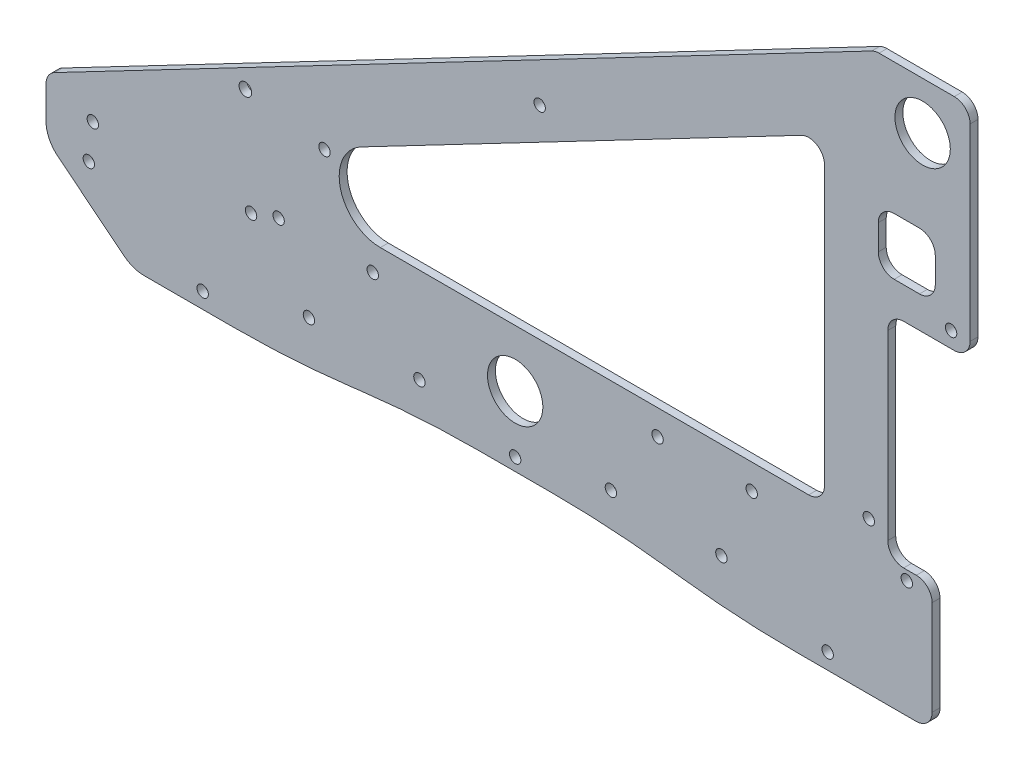
SolidWorks part; units mm, degrees
ref_plane "Front Plane" through (0, 0, 0) normal (0, 0, 1) x (1, 0, 0)
ref_plane "Top Plane" through (0, 0, 0) normal (0, 1, 0) x (1, 0, 0)
ref_plane "Right Plane" through (0, 0, 0) normal (1, 0, 0) x (0, 0, -1)
sketch "Sketch1" plane through (0, 0, 0) normal (0, 0, 1) x (1, 0, 0)
  line L1 (0, 0) -> (-355.6, 0)
  line L2 (0, 0) -> (0, 50.8)
  line L3 (0, 50.8) -> (-355.6, 50.8)
  line L4 (-355.6, 0) -> (-355.6, 50.8)
  line L5 (-167.3225, 6.35) -> (-167.3225, 34.29) construction
  line L6 (-292.735, 6.35) -> (-41.91, 6.35) construction
  circle A0 centre (-41.91, 6.35) radius 2.286
  circle A2 centre (-292.735, 6.35) radius 2.286
  circle A5 centre (-205.74, 19.05) radius 2.286
  circle A6 centre (-167.3225, 34.29) radius 11.1125
  circle A7 centre (-250.0852, 18.5066) radius 2.286
  circle A8 centre (-84.5598, 18.5066) radius 2.286
  circle A10 centre (-128.905, 19.05) radius 2.286
  circle A11 centre (-338.4153, 28.575) radius 2.286
  dimension "D3" = 125.4125
  dimension "D5" = 4.572
  dimension "D6" = 38.4175
  dimension "D9" = 15.7834
  dimension "D10" = 22.225
  dimension "D11" = 4.572
  dimension "D14" = 28.575
  dimension "D1" = 50.8
  dimension "D2" = 355.6
  dimension "D4" = 27.94
  dimension "D7" = 15.24
  dimension "D8" = 82.7627
  dimension "D12" = 167.3225
  dimension "D13" = 34.29
  dimension "D15" = 50.8
extrude "Bottom 2\"" add sketch "Sketch1" along normal blind 3.175
sketch "Sketch2" plane through (0, 0, 3.175) normal (0, 0, 1) x (1, 0, 0)
  line L0 (-384.175, 50.8) -> (-320.675, 0)
  line L1 (0, 50.8) -> (-355.6, 50.8) construction
  line L3 (-384.175, 50.8) -> (-384.175, 0)
  line L4 (-384.175, 0) -> (-320.675, 0)
  line L8 (0, 0) -> (-355.6, 0) construction
  dimension "D1" = 63.5
  dimension "D2" = 320.675
extrude "Cut-Extrude1" cut sketch "Sketch2" against normal through all
fillet "Fillet1" radius 12.7 2 edges at (-320.675, 0, 1.5875) (-355.6, 27.94, 1.5875)
sketch "Sketch3" plane through (0, 0, 3.175) normal (0, 0, 1) x (1, 0, 0)
  line L0 (-256.54, 0) -> (-205.74, 6.35)
  line L2 (-205.74, 6.35) -> (-128.905, 6.35)
  line L3 (-128.905, 6.35) -> (-78.105, 0)
  line L4 (-78.105, 0) -> (-256.54, 0)
  line L5 (0, 0) -> (-316.2201, 0) construction
  point P4 (-128.905, 19.05)
  point P7 (-205.74, 19.05)
  dimension "D1" = 50.8
  dimension "D2" = 50.8
  dimension "D3" = 12.7
extrude "Bottom Cutout" cut sketch "Sketch3" against normal through all
sketch "Sketch5" plane through (0, 0, 3.175) normal (0, 0, 1) x (1, 0, 0)
  line L0 (15.24, 50.8) -> (15.24, 224.79)
  line L1 (15.24, 224.79) -> (-22.86, 224.79)
  line L2 (-355.6, 50.8) -> (-22.86, 224.79)
  line L4 (0, 50.8) -> (-355.6, 50.8) construction
  line L5 (-355.6, 50.8) -> (15.24, 50.8)
  line L8 (0, 0) -> (-78.105, 0) construction
  line L9 (0, 0) -> (0, 50.8) construction
  circle A0 centre (-3.81, 205.74) radius 11.1125
  dimension "D3" = 22.225
  dimension "D1" = 38.1
  dimension "D2" = 19.05
  dimension "D4" = 205.74
  dimension "D5" = 3.81
  dimension "D6" = 19.05
extrude "Upper Triangle" add sketch "Sketch5" against normal up to surface (3.175 mm away) up to face at (-336.1293, 28.575, 0)
sketch "Sketch6" plane through (0, 0, 3.175) normal (0, 0, 1) x (1, 0, 0)
  circle A0 centre (-110.1725, 46.99) radius 2.286
  circle A1 centre (-167.3225, 11.43) radius 2.286
  circle A2 centre (-224.4725, 46.99) radius 2.286
  dimension "D1" = 4.572
  dimension "D2" = 114.3
  dimension "D3" = 46.99
  dimension "D4" = 110.1725
  dimension "D5" = 57.15
  dimension "D6" = 35.56
extrude "Gearbox Holes" cut sketch "Sketch6" against normal through all
sketch "Sketch7" plane through (0, 0, 3.175) normal (0, 0, 1) x (1, 0, 0)
  line L0 (0, 0) -> (0, 50.8) construction
  line L1 (0, 0) -> (-78.105, 0) construction
  circle A0 centre (-25.4, 60.96) radius 2.286
  dimension "D3" = 4.572
  dimension "D1" = 25.4
  dimension "D2" = 60.96
extrude "Cut-Extrude4" cut sketch "Sketch7" against normal through all
sketch "Sketch8" plane through (0, 0, 3.175) normal (0, 0, 1) x (1, 0, 0)
  line L0 (1.27, 172.085) -> (-21.59, 172.085)
  line L1 (15.24, 50.8) -> (-17.78, 50.8)
  line L2 (15.24, 50.8) -> (15.24, 136.525)
  line L4 (-17.78, 50.8) -> (-17.78, 136.525)
  line L5 (-17.78, 136.525) -> (15.24, 136.525)
  line L6 (-22.86, 224.79) -> (-355.6, 50.8) construction
  line L7 (0, 0) -> (-78.105, 0) construction
  line L8 (15.24, 224.79) -> (-22.86, 224.79) construction
  line L9 (-43.18, 185.5017) -> (-43.18, 57.15)
  line L10 (-43.18, 57.15) -> (-288.641, 57.15)
  line L11 (-288.641, 57.15) -> (-43.18, 185.5017)
  line L12 (-256.54, 0) -> (-316.2201, 0) construction
  line L13 (15.24, 50.8) -> (15.24, 224.79) construction
  line L14 (15.24, 50.8) -> (15.24, 224.79) construction
  line L15 (1.27, 172.085) -> (1.27, 149.225)
  line L16 (-21.59, 172.085) -> (-21.59, 149.225)
  line L17 (1.27, 149.225) -> (-21.59, 149.225)
  circle A1 centre (7.62, 142.875) radius 2.286
  circle A2 centre (-157.48, 138.6325) radius 2.286
  point P19 (-25.4, 60.96)
  dimension "D14" = 22.86
  dimension "D16" = 4.572
  dimension "D1" = 7.62
  dimension "D2" = 50.8
  dimension "D3" = 88.265
  dimension "D4" = 57.15
  dimension "D5" = 25.4
  dimension "D6" = 25.4
  dimension "D7" = 22.86
  dimension "D9" = 12.7
  dimension "D10" = 13.97
  dimension "D12" = 6.35
  dimension "D13" = 7.62
  dimension "D15" = 11.43
  dimension "D17" = 114.3
extrude "Cut-Extrude5" cut sketch "Sketch8" against normal through all
sketch "Sketch9" plane through (0, 0, 0) normal (0, 0, -1) x (-1, 0, 0)
  circle A0 centre (10.16, 46.99) radius 2.286
  circle A1 centre (72.39, 46.99) radius 2.286
  dimension "D1" = 4.572
extrude "Cut-Extrude6" cut sketch "Sketch9" against normal through all
fillet "Fillet2" radius 6.35 7 edges at (-355.6, 50.8, 1.5875) (-43.18, 185.5017, 1.5875) (-43.18, 57.15, 1.5875) (-17.78, 136.525, 1.5875) (-22.86, 224.79, 1.5875) (15.24, 224.79, 1.5875) (15.24, 136.525, 1.5875)
fillet "Fillet3" radius 6.35 4 edges at (1.27, 149.225, 1.5875) (1.27, 172.085, 1.5875) (-21.59, 172.085, 1.5875) (-21.59, 149.225, 1.5875)
sketch "Sketch10" [suppressed] plane through (0, 0, 3.175) normal (0, 0, 1) x (1, 0, 0)
  line L0 (-355.6, 50.8) -> (-43.18, 50.8)
  line L1 (-43.18, 50.8) -> (-43.18, 149.225)
  line L3 (-43.18, 149.225) -> (15.24, 149.225)
  line L4 (15.24, 136.525) -> (15.24, 224.79) construction
  line L6 (15.24, 149.225) -> (15.24, 224.79)
  line L7 (15.24, 224.79) -> (-22.86, 224.79)
  line L8 (-22.86, 224.79) -> (-355.6, 50.8)
  line L9 (-43.18, 57.15) -> (-43.18, 185.5017) construction
  line L10 (-21.59, 149.225) -> (1.27, 149.225) construction
extrude "Cut-Extrude7" [suppressed] cut sketch "Sketch10" against normal blind 5.08
sketch "Sketch11" plane through (0, 0, -43.815) normal (0, 0, -1) x (-1, 0, 0)
  line L0 (43.18, 63.5) -> (43.18, 175.0156) construction
  line L2 (96.52, 50.8) -> (96.52, 86.995)
  line L3 (96.52, 86.995) -> (157.1625, 86.995)
  line L4 (157.1625, 50.8) -> (157.1625, 86.995)
  line L5 (167.3225, 111.252) -> (167.3225, 34.29) construction
  line L6 (177.4825, 50.8) -> (177.4825, 86.995)
  line L7 (238.125, 86.995) -> (177.4825, 86.995)
  line L8 (238.125, 50.8) -> (238.125, 86.995)
  line L10 (15.24, 149.225) -> (5.08, 149.225) construction
  line L11 (43.18, 149.225) -> (167.3712, 149.225)
  line L12 (167.3712, 149.225) -> (282.575, 88.9848)
  line L13 (282.575, 88.9848) -> (282.575, 50.8)
  line L14 (282.575, 50.8) -> (238.125, 50.8)
  line L15 (157.1625, 50.8) -> (177.4825, 50.8)
  line L16 (43.18, 149.225) -> (43.18, 50.8)
  line L17 (43.18, 50.8) -> (96.52, 50.8)
  line L18 (157.1625, 50.8) -> (177.4825, 50.8)
  line L19 (0, 0) -> (78.105, 0) construction
  line L20 (43.18, 63.5) -> (43.18, 175.0156) construction
  line L21 (352.1924, 52.5818) -> (24.2424, 224.0671) construction
  line L22 (52.4724, 180.6427) -> (288.641, 57.15) construction
  line L23 (43.18, 136.525) -> (136.8435, 136.525)
  line L24 (43.18, 136.525) -> (43.18, 63.5)
  line L25 (83.82, 94.615) -> (101.2835, 94.615)
  line L26 (136.8435, 136.525) -> (101.2835, 94.615)
  line L29 (43.18, 63.5) -> (83.82, 63.5)
  line L30 (83.82, 94.615) -> (83.82, 63.5)
  circle A0 centre (167.3225, 111.252) radius 10.16
  circle A1 centre (157.48, 138.6325) radius 2.286
  circle A2 centre (90.17, 88.265) radius 2.286
  dimension "D4" = 4.572
  dimension "D5" = 20.32
  dimension "D16" = 4.572
  dimension "D1" = 10.16
  dimension "D2" = 96.52
  dimension "D3" = 36.195
  dimension "D6" = 44.45
  dimension "D8" = 50.8
  dimension "D9" = 12.7
  dimension "D10" = 7.62
  dimension "D11" = 12.7
  dimension "D12" = 12.7
  dimension "D13" = 35.56
  dimension "D14" = 6.35
  dimension "D15" = 6.35
extrude "Boss-Extrude3" [suppressed] add sketch "Sketch11" against normal blind 3.175
sketch "Sketch16" plane through (0, 0, 3.175) normal (0, 0, 1) x (1, 0, 0)
  line L0 (-224.4725, 46.99) -> (-262.255, 46.99) construction
  line L1 (-110.1725, 46.99) -> (-72.39, 46.99) construction
  circle A0 centre (-262.255, 46.99) radius 2.286
  dimension "D1" = 4.572
extrude "Cut-Extrude12" cut sketch "Sketch16" against normal through all
fillet "Fillet11" radius 16.51 1 edges at (-288.641, 57.15, 1.5875)
sketch "Sketch19" plane through (0, 0, 3.175) normal (0, 0, 1) x (1, 0, 0)
  line L2 (-355.6, 34.0439) -> (-355.6, 46.9547) construction
  line L3 (-256.54, 0) -> (-316.2201, 0) construction
  circle A0 centre (-275.59, 85.09) radius 2.54
  circle A1 centre (-243.84, 80.01) radius 2.286
  dimension "D3" = 5.08
  dimension "D5" = 4.572
  dimension "D1" = 80.01
  dimension "D2" = 85.09
  dimension "D4" = 5.08
  dimension "D6" = 31.75
extrude "Cut-Extrude14" cut sketch "Sketch19" against normal through all
fillet "Fillet4" [suppressed] radius 5.08
fillet "Fillet5" [suppressed] radius 6.35
fillet "Fillet6" [suppressed] radius 762
fillet "Fillet7" radius 381 4 edges at (-256.54, 0, 1.5875) (-205.74, 6.35, 1.5875) (-128.905, 6.35, 1.5875) (-78.105, 0, 1.5875)
fillet "Fillet8" radius 6.35 3 edges at (0, 50.8, 1.5875) (0, 0, 1.5875) (-17.78, 50.8, 1.5875)
fillet "Fillet9" [suppressed] radius 6.35
sketch "Sketch12" plane through (0, 0, 3.175) normal (0, 0, 1) x (1, 0, 0)
  line L0 (0, 6.35) -> (0, 44.45) construction
  line L1 (-280.2602, 0) -> (-316.2201, 0) construction
  circle A0 centre (-336.804, 43.18) radius 2.286
  circle A1 centre (-273.304, 43.18) radius 2.286
  dimension "D4" = 4.572
  dimension "D5" = 63.5
  dimension "D1" = 336.804
  dimension "D2" = 43.18
  dimension "D3" = 2
extrude "Cut-Extrude8" cut sketch "Sketch12" against normal through all
sketch "Sketch14" [suppressed] plane through (0, 0, 3.175) normal (0, 0, 1) x (1, 0, 0)
  circle A0 centre (-258.953, 38.1) radius 2.286
  circle A1 centre (-258.953, 12.7) radius 2.286
  dimension "D1" = 4.572
extrude "Cut-Extrude10" [suppressed] cut sketch "Sketch14" against normal through all
fillet "Fillet10" [suppressed] radius 6.35
sketch "Sketch20" [suppressed] plane through (0, 0, 3.175) normal (0, 0, 1) x (1, 0, 0)
  circle A0 centre (-30.48, 142.875) radius 2.286
  circle A2 centre (7.62, 142.875) radius 2.286 construction
  point P3 (7.62, 142.875)
  dimension "D1" = 38.1
extrude "Cut-Extrude15" [suppressed] cut sketch "Sketch20" against normal through all
sketch "Sketch21" [suppressed] plane through (0, 0, 0) normal (0, 0, -1) x (-1, 0, 0)
  circle A0 centre (25.4, 88.265) radius 2.286
  point P2 (25.4, 60.96)
  dimension "D2" = 4.572
  dimension "D1" = 27.305
extrude "Cut-Extrude16" [suppressed] cut sketch "Sketch21" against normal through all
